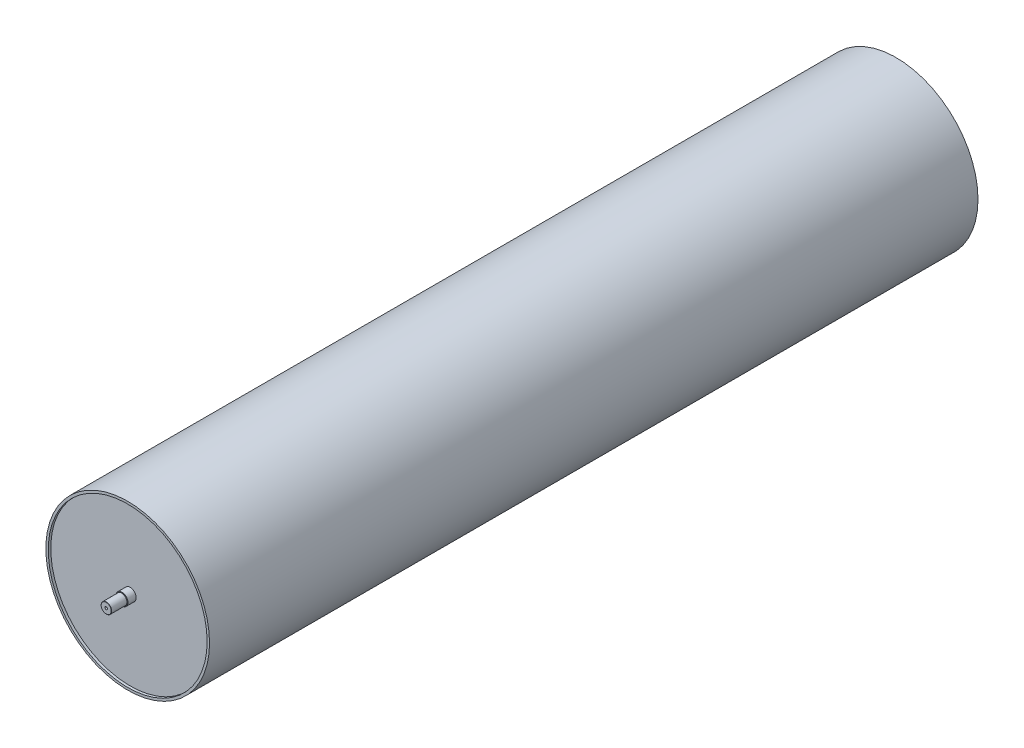
SolidWorks part; units mm, degrees
ref_plane "Front Plane" through (0, 0, 0) normal (0, 0, 1) x (1, 0, 0)
ref_plane "Top Plane" through (0, 0, 0) normal (0, 1, 0) x (1, 0, 0)
ref_plane "Right Plane" through (0, 0, 0) normal (1, 0, 0) x (0, 0, -1)
sketch "Sketch1" plane through (0, 0, 0) normal (0, 0, 1) x (1, 0, 0)
  circle A0 centre (0, 0) radius 165 construction
  circle A1 centre (0, 0) radius 158.7
  circle A2 centre (0, 0) radius 163.5
  dimension "D1" = 330
  dimension "D2" = 6.3
  dimension "D3" = 1.5
extrude "Boss-Extrude1" add sketch "Sketch1" along normal mid plane 1535
sketch "Sketch2" plane through (0, 0, 767.5) normal (0, 0, 1) x (1, 0, 0)
  circle A0 centre (0, 0) radius 158.7 construction
  circle A1 centre (0, 0) radius 158.7
extrude "Boss-Extrude2" add sketch "Sketch2" along normal blind 5 from offset 10 offset against normal yes
sketch "Sketch5" plane through (0, 0, 0) normal (1, 0, 0) x (0, 0, -1)
  line L0 (-779.5, 12) -> (779.5, 12)
  line L1 (779.5, 12) -> (779.5, 10.5)
  line L2 (779.5, 10.5) -> (810.5, 10.5)
  line L3 (810.5, 10.5) -> (810.5, 0)
  line L8 (810.5, 0) -> (-810.5, 0)
  line L9 (-810.5, 0) -> (-810.5, 10.5)
  line L14 (-810.5, 10.5) -> (-779.5, 10.5)
  line L15 (-779.5, 10.5) -> (-779.5, 12)
  line L16 (810.5, 0) -> (821, 0) construction
  line L18 (767.5, -163.5) -> (767.5, 163.5) construction
  point P20 (0, 12)
  dimension "D3" = 21
  dimension "D5" = 12
  dimension "D6" = 31
  dimension "D7" = 24
revolve "Revolve1" add sketch "Sketch5" angle 360 about L16
chamfer "Chamfer1" distance 0.5 4 edges at (0, -12, 779.5) (0, -12, -779.5) (0, -10.5, -810.5) (0, -10.5, 810.5)
hole_wizard "M6 Tapped Hole1" positions "Sketch6" profile "Sketch7" tap size "M6" standard "ISO"
sketch "Sketch6" plane through (0, 0, 810.5) normal (0, 0, 1) x (1, 0, 0)
  point P0 (0, 0)
sketch "Sketch7" plane through (0, 0, 810.5) normal (1, 0, 0) x (0, -1, 0)
  line L0 (0, 0) -> (0, 16.5022)
  line L1 (0, 16.5022) -> (2.5, 15)
  line L2 (2.5, 15) -> (2.5, 0)
  line L5 (2.5, 0) -> (0, 0)
  line L10 (0, 16.5022) -> (-2.5, 15) construction
  line L11 (0, -6.35) -> (0, 107.95) construction
  dimension "Tap Drill Dia." = 5
  dimension "Tap Drill Depth" = 15
  dimension "Drill Angle" = 118
cosmetic thread "Hole Thread1" parameters "D1"=12, "D2"=6
mirror "Mirror3" about plane through (0, 0, 0) normal (0, 0, 1) of "Boss-Extrude2"
sketch "Sketch8" plane through (0, 0, -810.5) normal (0, 0, -1) x (-1, 0, 0)
  circle A0 centre (0, 0) radius 7
  dimension "D1" = 14
extrude "Boss-Extrude3" add sketch "Sketch8" along normal blind 30
chamfer "Chamfer2" distance 0.5 1 edges at (0, 7, -840.5)
